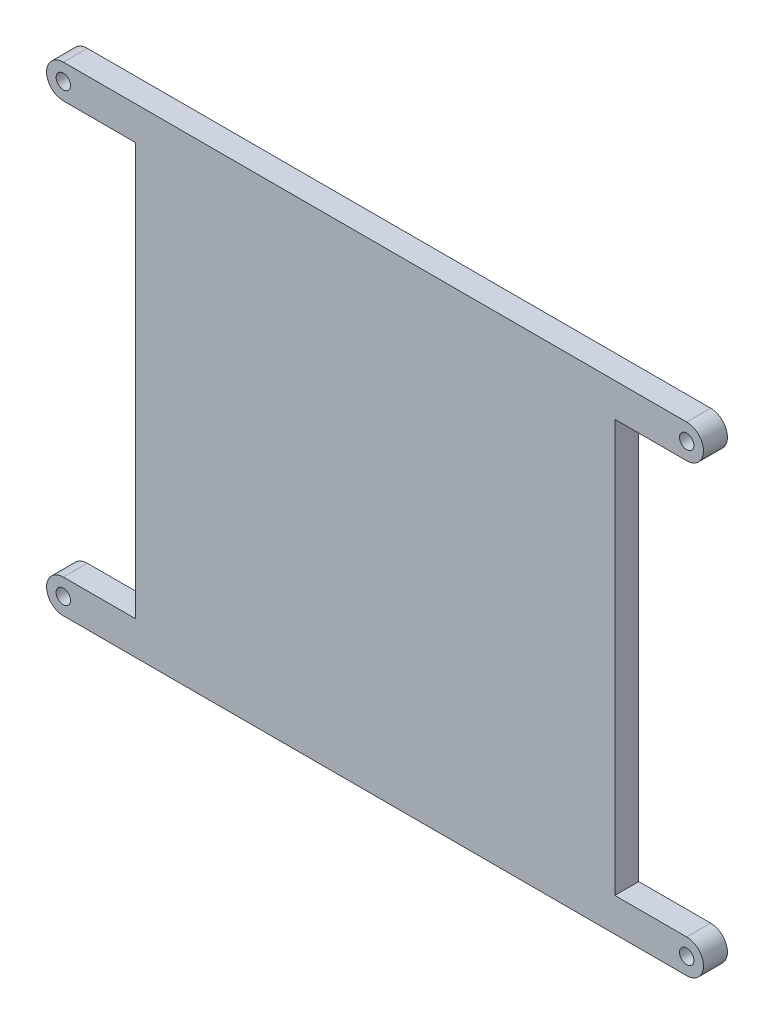
SolidWorks part; units mm, degrees
ref_plane "Plan de face" through (0, 0, 0) normal (0, 0, 1) x (1, 0, 0)
ref_plane "Plan de dessus" through (0, 0, 0) normal (0, 1, 0) x (1, 0, 0)
ref_plane "Plan de droite" through (0, 0, 0) normal (1, 0, 0) x (0, 0, -1)
sketch "Esquisse1" plane through (0, 0, 0) normal (0, 0, 1) x (1, 0, 0)
  line L0 (-50, 50) -> (-45, 50) construction
  line L8 (-50, -50) -> (50, -50)
  line L9 (-50, -43) -> (-50, 43)
  line L10 (-50, 50) -> (50, 50)
  line L11 (50, -43) -> (50, 43)
  line L12 (-50, -50) -> (50, 50) construction
  line L13 (-50, 50) -> (50, -50) construction
  line L14 (-50, 50) -> (-50, 43) construction
  line L15 (-50, 50) -> (-65, 50)
  line L17 (-65, 43) -> (-50, 43)
  line L18 (50, -50) -> (65, -50)
  line L20 (65, -43) -> (50, -43)
  line L21 (50, 50) -> (65, 50)
  line L24 (65, 43) -> (50, 43)
  line L25 (-50, -50) -> (-65, -50)
  line L26 (-65, -50) -> (-50, -50)
  line L27 (-65, -43) -> (-50, -43)
  circle A7 centre (-65, 46.5) radius 1.5
  arc A8 (-65, 50) -> (-65, 43) centre (-65, 46.5) ccw
  circle A9 centre (65, 46.5) radius 1.5
  arc A10 (65, 43) -> (65, 50) centre (65, 46.5) ccw
  circle A11 centre (65, -46.5) radius 1.5
  arc A12 (65, -50) -> (65, -43) centre (65, -46.5) ccw
  circle A13 centre (-65, -46.5) radius 1.5
  arc A14 (-65, -43) -> (-65, -50) centre (-65, -46.5) ccw
  point P15 (0, 0)
  dimension "D3" = 7
  dimension "D4" = 15
  dimension "D5" = 100
  dimension "D6" = 100
  dimension "D7" = 7
  dimension "D8" = 15
  dimension "D9" = 7
  dimension "D10" = 7
  dimension "D11" = 15
extrude "Boss.-Extru.1" add sketch "Esquisse1" along normal blind 5 contours L27 A14 L25 L8 L18 A12 L20 L11 L24 A10 L21 L10 L15 A8 L17 L9 A7 A9 A11 A13
